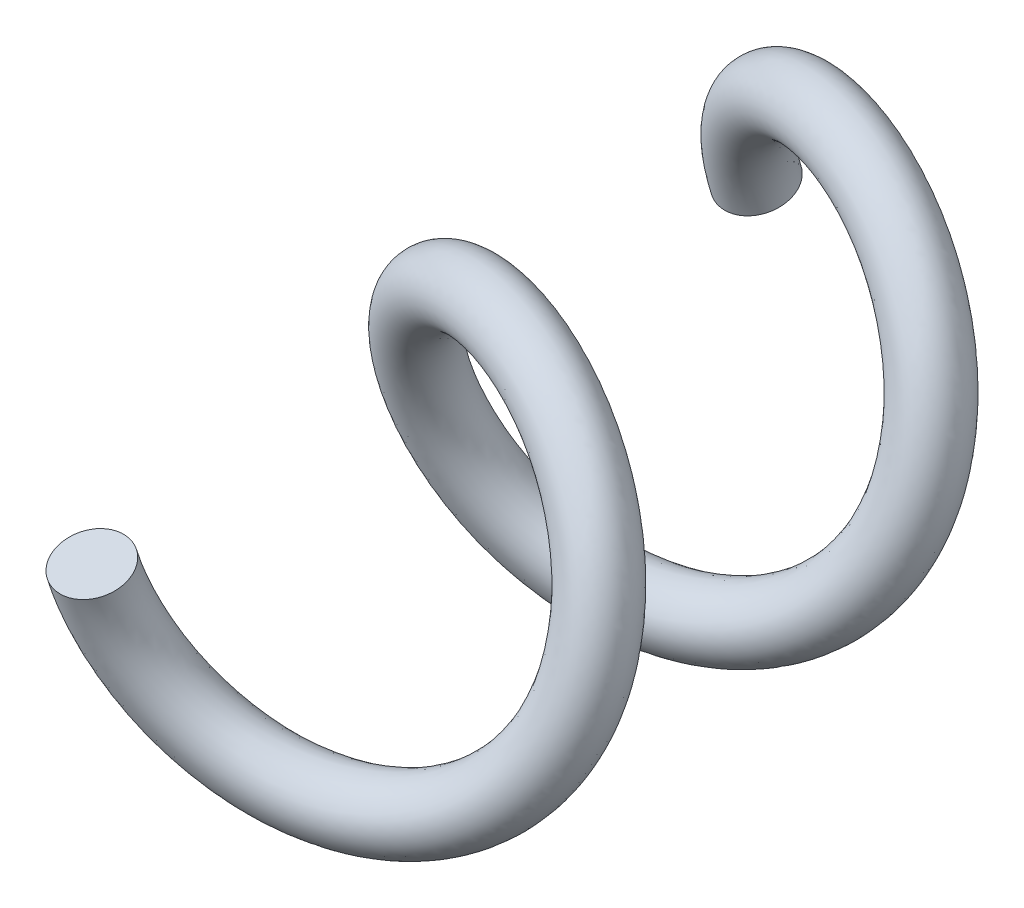
SolidWorks part; units mm, degrees
ref_plane "前视基准面" through (0, 0, 0) normal (0, 0, 1) x (1, 0, 0)
ref_plane "上视基准面" through (0, 0, 0) normal (0, 1, 0) x (1, 0, 0)
ref_plane "右视基准面" through (0, 0, 0) normal (1, 0, 0) x (0, 0, -1)
sketch "草图1" plane through (0, 0, 0) normal (0, 0, 1) x (1, 0, 0)
  circle A0 centre (0, 0) radius 50
curve "螺旋线/涡状线1" pitch 100 height 200 turns 2
ref_plane "基准面1" through (-50, 0, 0) normal (0, 0.9529, 0.3033) x (1, 0, 0)
sketch "草图5" plane through (-50, 0, 0) normal (0, 0.9529, 0.3033) x (1, 0, 0)
  circle A0 centre (-0.0072, 0) radius 10
sweep "扫描2" add profiles "草图5" path "螺旋线/涡状线1"
